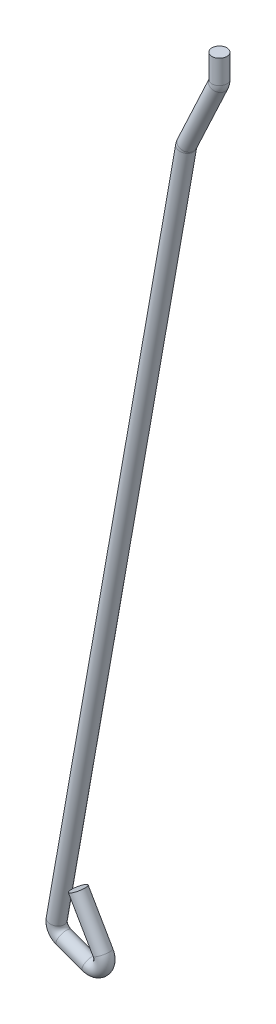
SolidWorks part; units mm, degrees
material "Brass"
ref_plane "Front Plane" through (0, 0, 0) normal (0, 0, 1) x (1, 0, 0)
ref_plane "Top Plane" through (0, 0, 0) normal (0, 1, 0) x (1, 0, 0)
ref_plane "Right Plane" through (0, 0, 0) normal (1, 0, 0) x (0, 0, -1)
sketch "Sketch1" plane through (0, 0, 0) normal (0, 0, 1) x (1, 0, 0)
  line L0 (0, 0) -> (0, -2.8934)
  line L1 (-0.119, -3.4302) -> (-3.9548, -11.656)
  line L2 (-4.0545, -11.9722) -> (-19.829, -101.4343)
  line L3 (-19.0127, -102.8482) -> (-15.8342, -104.0051)
  line L4 (-14.2999, -102.1767) -> (-17.3178, -96.9496)
  arc A0 (-0.119, -3.4302) -> (0, -2.8934) centre (-1.27, -2.8934) ccw
  arc A1 (-4.0545, -11.9722) -> (-3.9548, -11.656) centre (-2.8038, -12.1928) cw
  arc A2 (-19.829, -101.4343) -> (-19.0127, -102.8482) centre (-18.5783, -101.6548) ccw
  arc A3 (-15.8342, -104.0051) -> (-14.2999, -102.1767) centre (-15.3998, -102.8117) ccw
  point P10 (0, -3.175)
  point P13 (-4.0254, -11.8076)
  point P16 (-20.0141, -102.4838)
  point P19 (-12.5553, -105.1985)
  dimension "D10" = 1.27
  dimension "D1" = 10
  dimension "D2" = 25
  dimension "D3" = 110
  dimension "D4" = 40
  dimension "D5" = 3.175
  dimension "D6" = 9.525
  dimension "D7" = 92.075
  dimension "D8" = 7.9375
  dimension "D9" = 9.525
sketch "Sketch2" plane through (0, 0, 0) normal (0, 1, 0) x (1, 0, 0)
  line L0 (-0.119, 0) -> (0, 0) construction
  circle A0 centre (-0.0595, 0) radius 0.9144
  dimension "D1" = 1.8288
sweep "Sweep3" add profiles "Sketch2" path "Sketch1"
